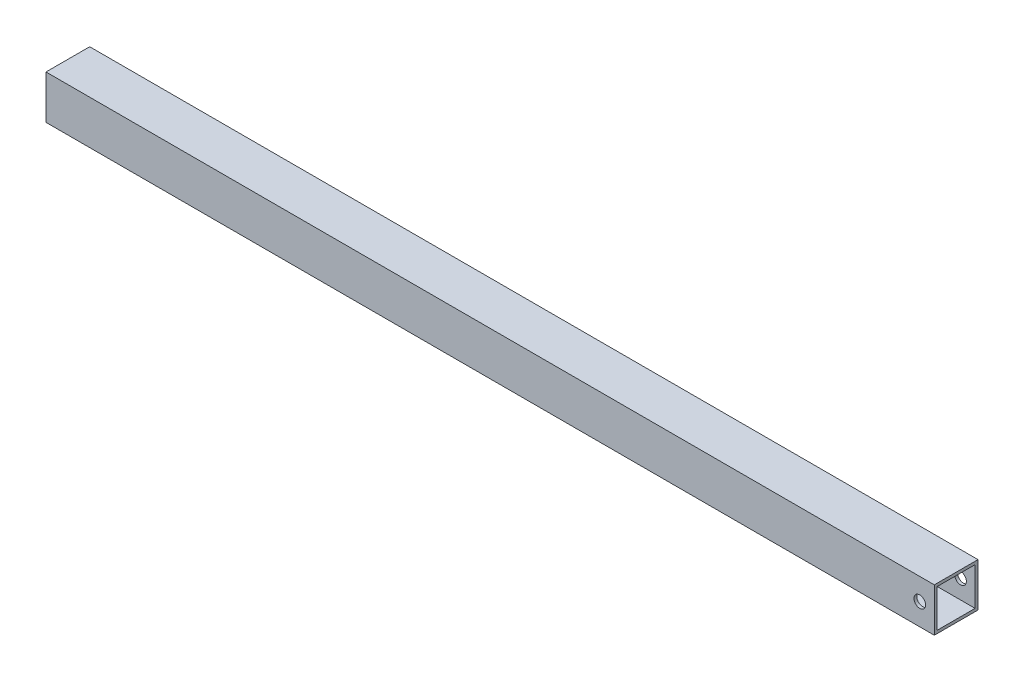
SolidWorks part; units mm, degrees
ref_plane "Front Plane" through (0, 0, 0) normal (0, 0, 1) x (1, 0, 0)
ref_plane "Top Plane" through (0, 0, 0) normal (0, 1, 0) x (1, 0, 0)
ref_plane "Right Plane" through (0, 0, 0) normal (1, 0, 0) x (0, 0, -1)
sketch "Sketch1" plane through (0, 0, 0) normal (1, 0, 0) x (0, 0, -1)
  line L1 (0, 0) -> (30, 0)
  line L2 (0, 0) -> (0, 30)
  line L3 (0, 30) -> (30, 30)
  line L4 (30, 0) -> (30, 30)
  line L5 (2, 2) -> (28, 2)
  line L6 (2, 2) -> (2, 28)
  line L7 (2, 28) -> (28, 28)
  line L8 (28, 2) -> (28, 28)
  dimension "D1" = 30
  dimension "D2" = 30
  dimension "D3" = 2
  dimension "D4" = 2
  dimension "D5" = 2
  dimension "D6" = 2
extrude "Boss-Extrude1" add sketch "Sketch1" along normal blind 610
ref_plane "Plane2" through (0, 130, 0) normal (0, 1, 0) x (1, 0, 0)
sketch "Sketch2" plane through (0, 0, 0) normal (0, 0, 1) x (1, 0, 0)
  line L0 (610, 30) -> (0, 30) construction
  line L1 (610, 30) -> (610, 0) construction
  circle A0 centre (600, 15) radius 4
  dimension "D1" = 8
  dimension "D2" = 15
  dimension "D3" = 10
extrude "Cut-Extrude1" cut sketch "Sketch2" against normal through all
